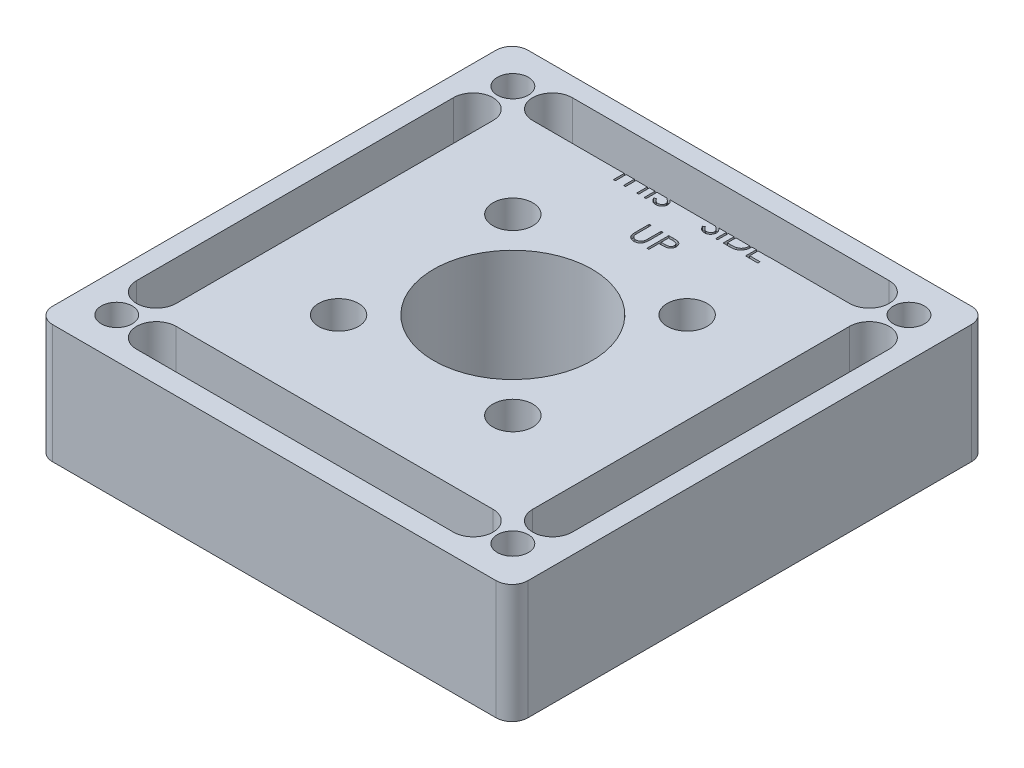
SolidWorks part; units mm, degrees
material "ABS PC"
ref_plane "Front Plane" through (0, 0, 0) normal (0, 0, 1) x (1, 0, 0)
ref_plane "Top Plane" through (0, 0, 0) normal (0, 1, 0) x (1, 0, 0)
ref_plane "Right Plane" through (0, 0, 0) normal (1, 0, 0) x (0, 0, -1)
sketch "Sketch1" plane through (0, 0, 0) normal (0, 1, 0) x (1, 0, 0)
  line L0 (3.1695, 50.4318) -> (3.1695, 88.3951) construction
  line L1 (3.1695, 88.3951) -> (41.2695, 88.3951)
  line L2 (41.2695, 88.3951) -> (41.2695, 12.1951)
  line L3 (41.2695, 12.1951) -> (-34.9305, 12.1951)
  line L4 (-34.9305, 12.1951) -> (-34.9305, 88.3951)
  line L5 (-34.9305, 88.3951) -> (3.1695, 88.3951)
  circle A1 centre (3.1695, 50.4318) radius 12.7
  dimension "D1" = 76.2
  dimension "D3" = 25.4
  dimension "D2" = 76.2
  dimension "D4" = 37.9633
extrude "Boss-Extrude2" add sketch "Sketch1" along normal blind 19.05
sketch "Sketch3" plane through (0, 19.05, 0) normal (0, 1, 0) x (1, 0, 0)
  line L0 (-10.8005, 64.4018) -> (17.1395, 64.4018) construction
  line L3 (17.1395, 36.4618) -> (-10.8005, 36.4618) construction
  line L4 (-10.8005, 36.4618) -> (-10.8005, 64.4018) construction
  line L5 (17.1395, 64.4018) -> (17.1395, 36.4618) construction
  circle A4 centre (17.1395, 36.4618) radius 3.2
  circle A5 centre (-10.8005, 36.4618) radius 3.2
  circle A6 centre (17.1395, 64.4018) radius 3.2
  circle A7 centre (-10.8005, 64.4018) radius 3.2
  point P11 (3.1695, 64.4018)
  dimension "D1" = 27.94
  dimension "D2" = 27.94
  dimension "D3" = 13.97
  dimension "D4" = 13.97
extrude "Cut-Extrude2" cut sketch "Sketch3" against normal blind 17.145
hole_wizard "Ø3.2 (3.2) Diameter Hole2" positions "Sketch6" profile "Sketch5" hole size "Ø3.2" standard "ANSI Metric" end condition through all
sketch "Sketch6" plane through (0, 1.905, 0) normal (0, 1, 0) x (1, 0, 0)
  point P12 (-10.8005, 64.4018)
  point P15 (17.1395, 64.4018)
  point P18 (17.1395, 36.4618)
  point P21 (-10.8005, 36.4618)
sketch "Sketch5" plane through (-10.8005, 1.905, -64.4018) normal (1, 0, 0) x (0, 0, 1)
  line L0 (0, 0) -> (0, 1.905)
  line L1 (0, 1.905) -> (1.6, 1.905)
  line L2 (1.6, 1.905) -> (1.6, 1.4)
  line L3 (1.6, 1.4) -> (3, 0)
  line L5 (3, 0) -> (0, 0)
  line L6 (-1.6, 1.4) -> (-3, 0) construction
  line L11 (0, -6.35) -> (0, 107.95) construction
  dimension "Thru Hole Dia." = 3.2
  dimension "Thru Hole Depth" = 1.905
  dimension "Near C'Sink Dia." = 6
  dimension "Near C'Sink Angle" = 90
sketch "Sketch7" plane through (0, 19.05, 0) normal (0, 1, 0) x (1, 0, 0)
  line L8 (3.1695, 50.4318) -> (34.9195, 50.4318) construction
  line L9 (34.9195, 50.4318) -> (34.9195, 82.1818) construction
  line L10 (34.9195, 82.1818) -> (-28.5805, 82.1818) construction
  line L11 (-28.5805, 82.1818) -> (-28.5805, 18.6818) construction
  line L12 (-28.5805, 18.6818) -> (34.9195, 18.6818) construction
  line L13 (34.9195, 18.6818) -> (34.9195, 50.4318) construction
  dimension "D1" = 31.75
  dimension "D5" = 31.75
  dimension "D6" = 63.5
  dimension "D7" = 63.5
  dimension "D8" = 63.5
hole_wizard "#10 Clearance Hole1" positions "Sketch8" profile "Sketch9" hole size "#10" standard "ANSI Inch" end condition through all
sketch "Sketch8" plane through (0, 19.05, 0) normal (0, 1, 0) x (1, 0, 0)
  point P0 (34.9195, 82.1818)
  point P3 (-28.5805, 82.1818)
  point P6 (-28.5805, 18.6818)
  point P9 (34.9195, 18.6818)
sketch "Sketch9" plane through (34.9195, 19.05, -82.1818) normal (1, 0, 0) x (0, 0, 1)
  line L0 (0, 0) -> (0, 19.05)
  line L1 (0, 19.05) -> (2.4892, 19.05)
  line L2 (2.4892, 19.05) -> (2.4892, 0)
  line L5 (2.4892, 0) -> (0, 0)
  line L11 (0, -6.35) -> (0, 107.95) construction
  dimension "Thru Hole Dia." = 4.9784
  dimension "Thru Hole Depth" = 19.05
sketch "Sketch10" plane through (0, 19.05, 0) normal (0, 1, 0) x (1, 0, 0)
  text T0 "THIS    SIDE\r\n       UP"
extrude "Cut-Extrude1" cut sketch "Sketch10" against normal blind 0.635
fillet "Fillet2" radius 2.54 4 edges at (-34.9305, 9.525, -12.1951) (41.2695, 9.525, -12.1951) (41.2695, 9.525, -88.3951) (-34.9305, 9.525, -88.3951)
sketch "Sketch11" plane through (0, 19.05, 0) normal (0, 1, 0) x (1, 0, 0)
  line L0 (-28.5805, 75.8318) -> (-28.5805, 25.0318) construction
  line L1 (-28.5805, 82.1818) -> (-28.5805, 18.6818) construction
  line L2 (-25.4055, 75.8318) -> (-25.4055, 25.0318)
  line L3 (-31.7555, 75.8318) -> (-31.7555, 25.0318)
  line L4 (-22.2305, 82.1818) -> (28.5695, 82.1818) construction
  line L5 (34.9195, 82.1818) -> (-28.5805, 82.1818) construction
  line L6 (-22.2305, 85.3568) -> (28.5695, 85.3568)
  line L7 (-22.2305, 79.0068) -> (28.5695, 79.0068)
  line L8 (34.9195, 75.8318) -> (34.9195, 25.0318) construction
  line L9 (34.9195, 18.6818) -> (34.9195, 50.4318) construction
  line L10 (38.0945, 75.8318) -> (38.0945, 25.0318)
  line L11 (31.7445, 75.8318) -> (31.7445, 25.0318)
  line L12 (28.5695, 18.6818) -> (-22.2305, 18.6818) construction
  line L13 (-28.5805, 18.6818) -> (34.9195, 18.6818) construction
  line L14 (28.5695, 15.5068) -> (-22.2305, 15.5068)
  line L15 (28.5695, 21.8568) -> (-22.2305, 21.8568)
  arc A0 (-25.4055, 75.8318) -> (-31.7555, 75.8318) centre (-28.5805, 75.8318) ccw
  arc A1 (-31.7555, 25.0318) -> (-25.4055, 25.0318) centre (-28.5805, 25.0318) ccw
  arc A2 (-22.2305, 85.3568) -> (-22.2305, 79.0068) centre (-22.2305, 82.1818) ccw
  arc A3 (28.5695, 79.0068) -> (28.5695, 85.3568) centre (28.5695, 82.1818) ccw
  arc A4 (38.0945, 75.8318) -> (31.7445, 75.8318) centre (34.9195, 75.8318) ccw
  arc A5 (31.7445, 25.0318) -> (38.0945, 25.0318) centre (34.9195, 25.0318) ccw
  arc A6 (28.5695, 15.5068) -> (28.5695, 21.8568) centre (28.5695, 18.6818) ccw
  arc A7 (-22.2305, 21.8568) -> (-22.2305, 15.5068) centre (-22.2305, 18.6818) ccw
  point P4 (-28.5805, 50.4318)
  point P13 (3.1695, 82.1818)
  point P23 (34.9195, 50.4318)
  point P32 (3.1695, 18.6818)
extrude "Cut-Extrude3" cut sketch "Sketch11" against normal blind 50.8
